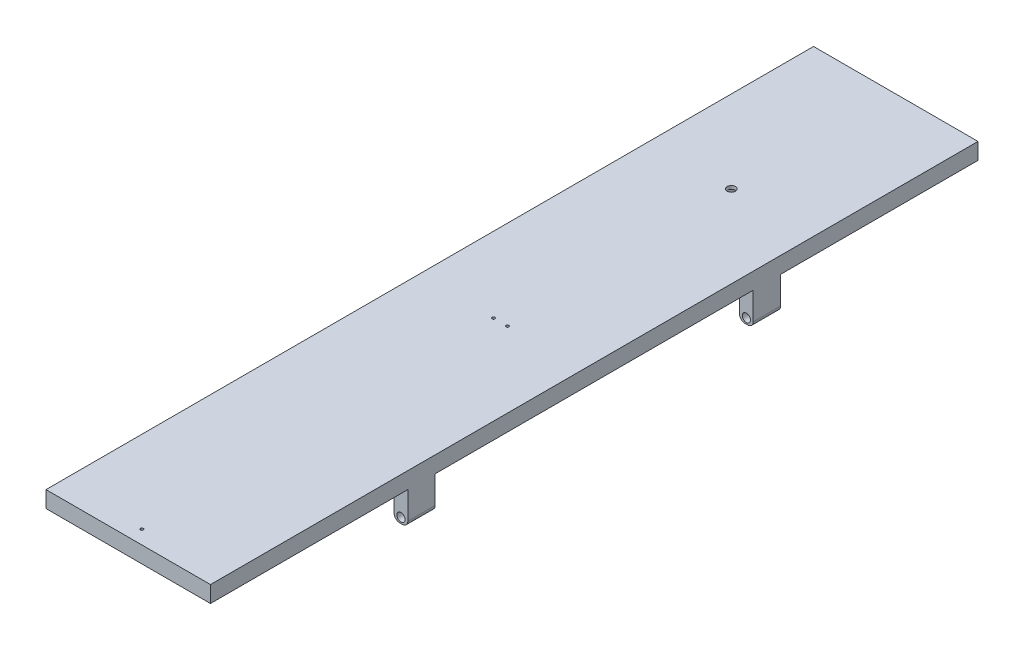
SolidWorks part; units mm, degrees
ref_plane "Front Plane" through (0, 0, 0) normal (0, 0, 1) x (1, 0, 0)
ref_plane "Top Plane" through (0, 0, 0) normal (0, 1, 0) x (1, 0, 0)
ref_plane "Right Plane" through (0, 0, 0) normal (1, 0, 0) x (0, 0, -1)
sketch "Sketch1" plane through (0, 0, 0) normal (0, 0, 1) x (1, 0, 0)
  line L0 (0, 0) -> (0, 30)
  line L1 (0, 30) -> (-300, 30)
  line L2 (-25, 0) -> (-275, 0)
  line L3 (-300, 0) -> (-300, 30)
  line L4 (0, 0) -> (0, -50)
  line L5 (-10, -60) -> (-15, -60)
  line L6 (-25, -50) -> (-25, 0)
  line L8 (-150, 30) -> (-150, -148.6923) construction
  line L9 (-290, -60) -> (-285, -60)
  line L10 (-300, 0) -> (-300, -50)
  line L11 (-275, -50) -> (-275, 0)
  circle A0 centre (-12.5, -50) radius 7.5
  arc A1 (0, -50) -> (-10, -60) centre (-10, -50) cw
  arc A2 (-15, -60) -> (-25, -50) centre (-15, -50) cw
  arc A3 (-285, -60) -> (-275, -50) centre (-285, -50) ccw
  arc A4 (-300, -50) -> (-290, -60) centre (-290, -50) ccw
  circle A5 centre (-287.5, -50) radius 7.5
  point P14 (-25, -60)
  dimension "D3" = 15
  dimension "D4" = 12.5
  dimension "D5" = 50
  dimension "D8" = 10
  dimension "D9" = 30
  dimension "D1" = 300
  dimension "D2" = 30
  dimension "D6" = 60
  dimension "D7" = 25
extrude "Boss-Extrude1" add sketch "Sketch1" along normal blind 1100 and the other way blind 300
sketch "Sketch3" plane through (0, 0, 0) normal (1, 0, 0) x (0, 0, -1)
  line L0 (-1100, 0) -> (-740, 0)
  line L1 (-1100, -50) -> (-1100, 30) construction
  line L2 (-740, 0) -> (-740, -60)
  line L3 (-1100, -60) -> (300, -60) construction
  line L4 (-740, -60) -> (-1100, -60)
  line L5 (-1100, -60) -> (-1100, 0)
  line L6 (0, 0) -> (300, 0)
  line L7 (0, 0) -> (-1100, 0) construction
  line L10 (-60, 0) -> (-60, -60)
  line L11 (-60, -60) -> (0, -60)
  line L12 (0, 0) -> (-60, 0)
  line L14 (-690, -60) -> (-110, -60)
  line L17 (-690, -60) -> (-690, -50)
  line L18 (-1100, -50) -> (300, -50) construction
  line L20 (-110, -50) -> (-110, -60)
  line L21 (300, 0) -> (300, -60)
  line L22 (300, -60) -> (0, -60)
  line L23 (-110, -50) -> (-110, 0)
  line L24 (-110, 0) -> (-690, 0)
  line L25 (-690, 0) -> (-690, -50)
  line L27 (300, -50) -> (300, 30) construction
  point P14 (-550, 0)
  dimension "D1" = 580
  dimension "D2" = 410
  dimension "D3" = 50
  dimension "D4" = 50
  dimension "D5" = 60
  dimension "D6" = 60
extrude "Cut-Extrude1" cut sketch "Sketch3" against normal through all and the other way through all
sketch "Sketch4" plane through (0, 30, 0) normal (0, 1, 0) x (1, 0, 0)
  line L0 (0, 300) -> (-300, 300) construction
  line L1 (-150, 300) -> (-150, -1100) construction
  line L2 (0, -1100) -> (-300, -1100) construction
  circle A0 centre (-150, 0) radius 7.5
  dimension "D1" = 15
  dimension "D2" = 1100
extrude "Cut-Extrude2" cut sketch "Sketch4" against normal through all
sketch "Sketch7" plane through (0, 0, 0) normal (0, -1, 0) x (-1, 0, 0)
  line L1 (162.5, -16) -> (137.5, -16)
  line L2 (162.5, -16) -> (162.5, 16)
  line L3 (162.5, 16) -> (137.5, 16)
  line L4 (137.5, -16) -> (137.5, 16)
  line L5 (162.5, -16) -> (137.5, 16) construction
  line L6 (162.5, 16) -> (137.5, -16) construction
  point P0 (150, 0)
  dimension "D1" = 25
  dimension "D2" = 32
extrude "Boss-Extrude2" add sketch "Sketch7" along normal blind 37.5
sketch "Sketch8" plane through (0, 0, 16) normal (0, 0, 1) x (1, 0, 0)
  line L5 (-137.5, 0) -> (-162.5, 0) construction
  line L6 (-158, 0) -> (-142, 0)
  line L7 (-158, 0) -> (-158, -32.5)
  line L8 (-158, -32.5) -> (-142, -32.5)
  line L9 (-142, 0) -> (-142, -32.5)
  line L10 (-162.5, -37.5) -> (-162.5, 0) construction
  dimension "D1" = 16
  dimension "D2" = 4.5
  dimension "D3" = 32.5
extrude "Cut-Extrude4" cut sketch "Sketch8" against normal through all
sketch "Sketch9" plane through (0, 0, 0) normal (0, -1, 0) x (1, 0, 0)
  line L1 (-158, 32) -> (-142, 32)
  line L2 (-158, 32) -> (-158, -32)
  line L3 (-158, -32) -> (-142, -32)
  line L4 (-142, 32) -> (-142, -32)
  line L5 (-158, 32) -> (-142, -32) construction
  line L6 (-158, -32) -> (-142, 32) construction
  point P0 (-150, 0)
  dimension "D1" = 16
  dimension "D2" = 64
extrude "Cut-Extrude5" cut sketch "Sketch9" against normal blind 24
sketch "Sketch10" plane through (0, 30, 0) normal (0, 1, 0) x (1, 0, 0)
  line L0 (-150, -1100) -> (-150, 300) construction
  line L1 (0, -1100) -> (-300, -1100) construction
  line L2 (0, 300) -> (-300, 300) construction
  line L3 (-162.7, -420.95) -> (-137.3, -420.95) construction
  line L4 (-300, -375) -> (0, -375) construction
  line L5 (-300, 300) -> (-300, -1100) construction
  line L6 (0, 300) -> (0, -1100) construction
  circle A0 centre (-150, -1075) radius 2.5908
  circle A1 centre (-162.7, -420.95) radius 2.5908
  circle A3 centre (-137.3, -420.95) radius 2.5908
  dimension "D1" = 5.1816
  dimension "D2" = 5.1816
  dimension "D3" = 12.7
  dimension "D4" = 5.1816
  dimension "D5" = 25.4
  dimension "D6" = 700
  dimension "D7" = 654.05
  dimension "D8" = 675
extrude "Cut-Extrude6" cut sketch "Sketch10" against normal blind 20
